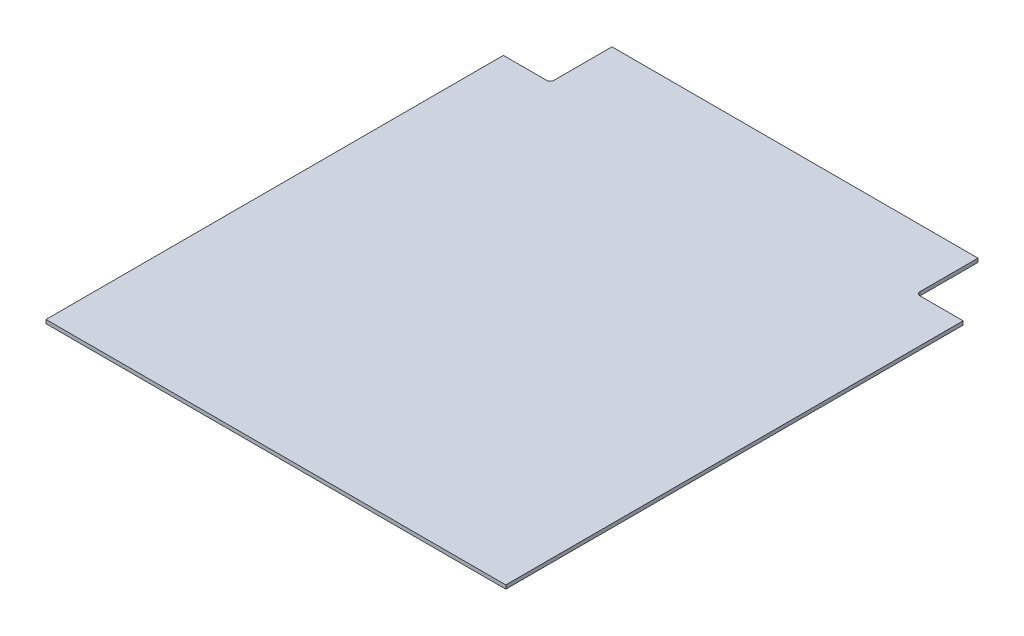
SolidWorks part; units mm, degrees
material "6061-T6 (SS)"
ref_plane "Front" through (0, 0, 0) normal (0, 0, 1) x (1, 0, 0)
ref_plane "Top" through (0, 0, 0) normal (0, 1, 0) x (1, 0, 0)
ref_plane "Right" through (0, 0, 0) normal (1, 0, 0) x (0, 0, -1)
sketch "Sketch1" plane through (0, 0, 0) normal (0, 1, 0) x (1, 0, 0)
  line L1 (196.85, -222.25) -> (-196.85, -222.25)
  line L2 (196.85, -222.25) -> (196.85, 222.25)
  line L3 (196.85, 222.25) -> (-196.85, 222.25)
  line L4 (-196.85, -222.25) -> (-196.85, 222.25)
  line L5 (196.85, -222.25) -> (-196.85, 222.25) construction
  line L6 (196.85, 222.25) -> (-196.85, -222.25) construction
  point P0 (0, 0)
  dimension "D1" = 393.7
  dimension "D2" = 444.5
extrude "Boss-Extrude1" add sketch "Sketch1" along normal blind 3.175
sketch "Sketch2" plane through (0, 3.175, 0) normal (0, 1, 0) x (1, 0, 0)
  line L0 (196.85, 222.25) -> (-196.85, 222.25) construction
  line L1 (-196.85, 222.25) -> (-156.718, 222.25)
  line L2 (-196.85, 222.25) -> (-196.85, 169.418)
  line L3 (-196.85, 169.418) -> (-159.893, 169.418)
  line L4 (-156.718, 222.25) -> (-156.718, 172.593)
  line L5 (196.85, 222.25) -> (156.718, 222.25)
  line L6 (196.85, 222.25) -> (196.85, 169.418)
  line L7 (196.85, 169.418) -> (159.893, 169.418)
  line L8 (156.718, 222.25) -> (156.718, 172.593)
  arc A0 (-156.718, 172.593) -> (-159.893, 169.418) centre (-159.893, 172.593) cw
  arc A1 (156.718, 172.593) -> (159.893, 169.418) centre (159.893, 172.593) ccw
  dimension "D1" = 3.175
  dimension "D2" = 52.832
  dimension "D3" = 40.132
extrude "Cut-Extrude1" cut sketch "Sketch2" against normal blind 10
